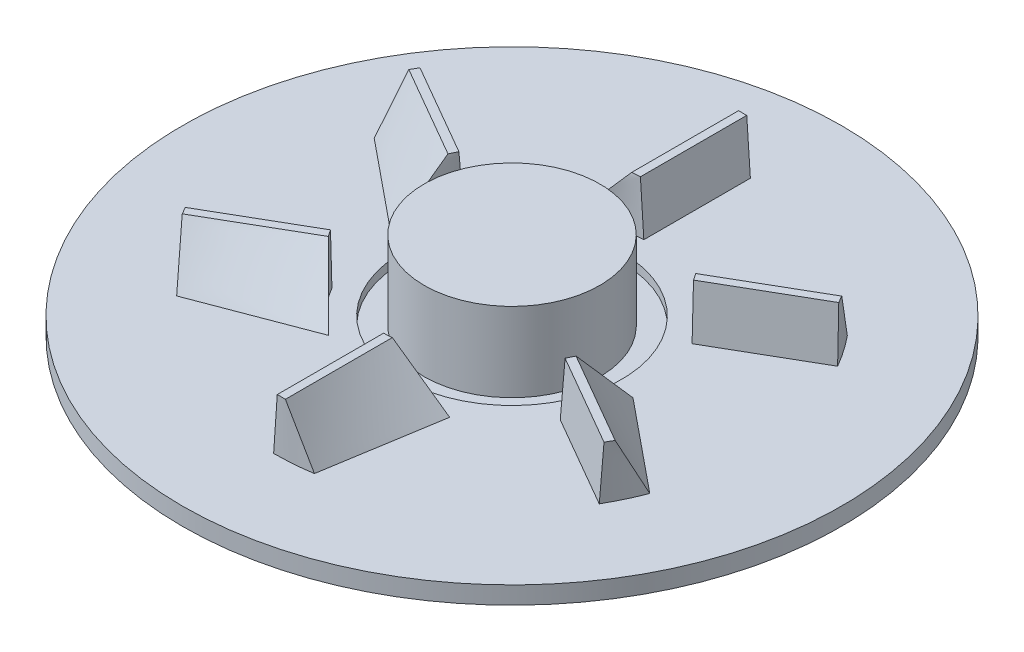
SolidWorks part; units mm, degrees
ref_plane "Front Plane" through (0, 0, 0) normal (0, 0, 1) x (1, 0, 0)
ref_plane "Top Plane" through (0, 0, 0) normal (0, 1, 0) x (1, 0, 0)
ref_plane "Right Plane" through (0, 0, 0) normal (1, 0, 0) x (0, 0, -1)
sketch "Sketch2" plane through (0, 0, 0) normal (0, 1, 0) x (1, 0, 0)
  circle A0 centre (0, 0) radius 37.5
  dimension "D1" = 75
extrude "Boss-Extrude1" add sketch "Sketch2" along normal blind 2
sketch "Sketch3" plane through (0, 2, 0) normal (0, 1, 0) x (1, 0, 0)
  line L0 (0, -15) -> (0, -27.1243)
  line L1 (6.4478, -13.5435) -> (4.3017, -26.781)
  arc A0 (0, -15) -> (6.4478, -13.5435) centre (0, 0) ccw
  arc A1 (0, -27.1243) -> (4.3017, -26.781) centre (0, 0) ccw
ref_plane "Plane1" through (0, 8, 0) normal (0, 1, 0) x (1, 0, 0)
sketch "Sketch4" plane through (0, 8, 0) normal (0, 1, 0) x (1, 0, 0)
  line L0 (0.4, -15.0122) -> (0.4, -27.1123)
  line L1 (1.3298, -27.1144) -> (1.3298, -14.9469)
  line L2 (1.3298, -14.9469) -> (0.4, -15.0122)
  arc A0 (0.4, -27.1123) -> (1.3298, -27.1144) centre (0.8301, -42.4739) cw
  dimension "D1" = 0.4
loft "Loft1" add profiles "Sketch3", "Sketch4"
sketch "Sketch5" plane through (0, 0, 0) normal (0, 0, 1) x (1, 0, 0)
  line L0 (0, -1000) -> (0, 49000) construction
pattern_circular "CirPattern1" count 6 over 360 about axis through (0, -1000, 0) along (0, 1, 0) of "Loft1"
sketch "Sketch6" plane through (0, 2, 0) normal (0, 1, 0) x (1, 0, 0)
  circle A0 centre (0, 0) radius 12.5
  dimension "D1" = 25
extrude "Cut-Extrude1" cut sketch "Sketch6" against normal blind 1
sketch "Sketch7" plane through (0, 1, 0) normal (0, 1, 0) x (1, 0, 0)
  circle A0 centre (0, 0) radius 10
  dimension "D1" = 20
extrude "Boss-Extrude2" add sketch "Sketch7" along normal blind 9
sketch "Sketch8" plane through (0, 0, 0) normal (0, -1, 0) x (1, 0, 0)
  circle A0 centre (0, 0) radius 5
  dimension "D1" = 10
extrude "Cut-Extrude2" cut sketch "Sketch8" against normal blind 8
